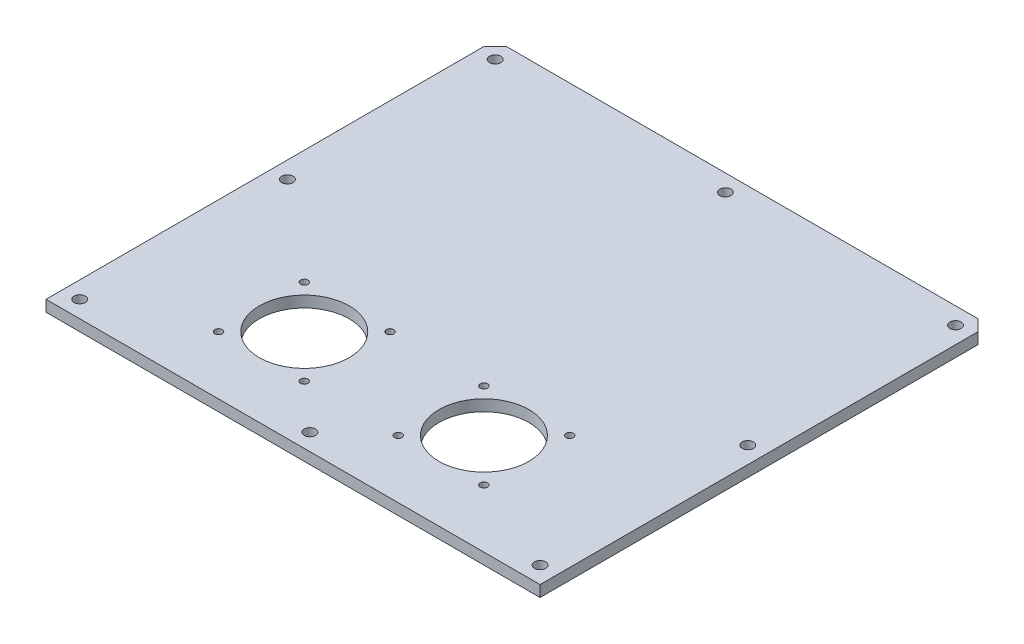
SolidWorks part; units mm, degrees
ref_plane "Спереди" through (0, 0, 0) normal (0, 0, 1) x (1, 0, 0)
ref_plane "Сверху" through (0, 0, 0) normal (0, 1, 0) x (1, 0, 0)
ref_plane "Справа" through (0, 0, 0) normal (1, 0, 0) x (0, 0, -1)
sketch "Sketch1" plane through (0, 0, 0) normal (0, 1, 0) x (1, 0, 0)
  line L0 (110, -150) -> (110, 50)
  line L1 (0, 50) -> (-110, 50)
  line L2 (-110, 50) -> (-110, -150)
  line L3 (-110, -150) -> (110, -150)
  line L4 (110, 50) -> (0, 50)
  line L5 (-110, 50) -> (-102.5, 50)
  line L6 (-102.5, 50) -> (-102.5, 42.5)
  circle A0 centre (-102.5, 42.5) radius 3
  circle A1 centre (-34.33, 42.5) radius 3
  circle A2 centre (33.84, 42.5) radius 3
  circle A3 centre (102.01, 42.5) radius 3
  circle A4 centre (-34.33, -142.5) radius 3
  circle A5 centre (33.84, -142.5) radius 3
  circle A6 centre (102.01, -142.5) radius 3
  circle A7 centre (-102.5, -142.5) radius 3
  circle A8 centre (-102.5, -19.17) radius 3
  circle A9 centre (-102.5, -80.84) radius 3
  circle A10 centre (102.5, -19.17) radius 3
  circle A11 centre (102.5, -80.84) radius 3
  circle A12 centre (102.5, 42.5) radius 3
  dimension "D1" = 4
  dimension "D2" = 2
  dimension "D3" = 3
  dimension "D4" = 2
extrude "Boss-Extrude1" add sketch "Sketch1" along normal blind 5
chamfer "Chamfer1" distance 5 angle 45 2 edges at (110, 2.5, -50) (-110, 2.5, -50)
sketch "Sketch4" plane through (0, 0, 0) normal (0, -1, 0) x (1, 0, 0)
  line L1 (0, 130) -> (-90, 130)
  line L2 (0, 135) -> (95, 135)
  line L3 (95, 135) -> (95, -35)
  line L4 (95, -35) -> (-95, -35)
  line L5 (-95, -35) -> (-95, 135)
  line L6 (-95, 135) -> (0, 135)
  line L7 (-90, 130) -> (-90, -30)
  line L8 (-90, -30) -> (90, -30)
  line L9 (90, -30) -> (90, 130)
  line L10 (90, 130) -> (0, 130)
extrude "Boss-Extrude5" add sketch "Sketch4" along normal blind 5
chamfer "Chamfer2" distance 2 angle 45 4 edges at (0, -5, -35) (95, -5, 50) (-95, -5, 50) (0, -5, 135)
sketch "Sketch9" plane through (0, 5, 0) normal (0, 1, 0) x (1, 0, 0)
  circle A0 centre (40, -105) radius 20
  circle A1 centre (-40, -105) radius 20
  circle A2 centre (59.0919, -85.9081) radius 2
  circle A3 centre (59.0919, -124.0919) radius 2
  circle A4 centre (20.9081, -124.0919) radius 2
  circle A5 centre (20.9081, -85.9081) radius 2
  circle A6 centre (-20.9081, -85.9081) radius 2
  circle A7 centre (-20.9081, -124.0919) radius 2
  circle A8 centre (-59.0919, -124.0919) radius 2
  circle A9 centre (-59.0919, -85.9081) radius 2
  point P0 (-20.9081, -85.9081)
  point P1 (59.0919, -85.9081)
  point P2 (-40, -105)
  point P16 (40, -105)
  point P29 (40, -105)
  point P37 (-40, -105)
extrude "Cut-Extrude4" cut sketch "Sketch9" against normal blind 5 contours A1 | A0
sketch "Sketch10" plane through (0, 5, 0) normal (0, 1, 0) x (1, 0, 0)
  line L0 (110, 45) -> (110, 42.5)
  line L1 (110, -150) -> (110, 45) construction
  circle A0 centre (-102.5, 42.5) radius 3
  circle A1 centre (0, 42.5) radius 3
  circle A2 centre (102.5, 42.5) radius 3
  circle A3 centre (102.5, 42.5) radius 3
  circle A4 centre (102.5, -50) radius 3
  circle A5 centre (-102.5, -50) radius 3
  circle A6 centre (-102.5, -142.5) radius 3
  circle A7 centre (0, -142.5) radius 3
  circle A8 centre (102.5, -142.5) radius 3
  dimension "D1" = 3
  dimension "D2" = 2
  dimension "D3" = 2
  dimension "D4" = 2
hole_wizard "M6 Tapped Hole1" positions "Sketch11" profile "Sketch13" tap size "M6" standard "ISO" end condition through all
sketch "Sketch11" plane through (0, 5, 0) normal (0, 1, 0) x (1, 0, 0)
  point P0 (-102.5, 42.5)
  point P3 (0, 42.5)
  point P6 (102.5, 42.5)
  point P9 (102.5, -50)
  point P12 (-102.5, -50)
  point P16 (-102.5, -142.5)
  point P19 (0, -142.5)
  point P22 (102.5, -142.5)
sketch "Sketch13" plane through (-102.5, 5, -42.5) normal (1, 0, 0) x (0, 0, 1)
  line L0 (0, 0) -> (0, 10)
  line L1 (0, 10) -> (2.5, 10)
  line L2 (2.5, 10) -> (2.5, 0)
  line L5 (2.5, 0) -> (0, 0)
  line L11 (0, -6.35) -> (0, 107.95) construction
  dimension "Thru Tap Drill Dia." = 5
  dimension "Thru Tap Drill Depth" = 10
cosmetic thread "Hole Thread1" parameters "D2"=6
cosmetic thread "Hole Thread2" parameters "D2"=6
cosmetic thread "Hole Thread3" parameters "D2"=6
cosmetic thread "Hole Thread4" parameters "D2"=6
cosmetic thread "Hole Thread5" parameters "D2"=6
cosmetic thread "Hole Thread14" parameters "D2"=6
cosmetic thread "Hole Thread15" parameters "D2"=6
cosmetic thread "Hole Thread16" parameters "D2"=6
sketch "Sketch15" plane through (0, 5, 0) normal (0, 1, 0) x (1, 0, 0)
  circle A1 centre (-59.0919, -85.9081) radius 2
  circle A2 centre (-20.9081, -85.9081) radius 2
  circle A3 centre (-20.9081, -124.0919) radius 2
  circle A4 centre (-59.0919, -124.0919) radius 2
  circle A5 centre (20.9081, -124.0919) radius 2
  circle A6 centre (20.9081, -85.9081) radius 2
  circle A7 centre (59.0919, -124.0919) radius 2
  circle A8 centre (59.0919, -85.9081) radius 2
  dimension "D1" = 4
hole_wizard "M4 Tapped Hole1" positions "Sketch18" profile "Sketch19" tap size "M4" standard "ISO"
sketch "Sketch18" plane through (0, 5, 0) normal (0, 1, 0) x (1, 0, 0)
  point P0 (-59.0919, -85.9081)
  point P3 (-20.9081, -85.9081)
  point P6 (-20.9081, -124.0919)
  point P9 (-59.0919, -124.0919)
  point P12 (20.9081, -85.9081)
  point P15 (59.0919, -85.9081)
  point P18 (59.0919, -124.0919)
  point P21 (20.9081, -124.0919)
sketch "Sketch19" plane through (-59.0919, 5, 85.9081) normal (1, 0, 0) x (0, 0, 1)
  line L0 (0, 0) -> (0, 5.9914)
  line L1 (0, 5.9914) -> (1.65, 5)
  line L2 (1.65, 5) -> (1.65, 0)
  line L5 (1.65, 0) -> (0, 0)
  line L10 (0, 5.9914) -> (-1.65, 5) construction
  line L11 (0, -6.35) -> (0, 107.95) construction
  dimension "Tap Drill Dia." = 3.3
  dimension "Tap Drill Depth" = 5
  dimension "Drill Angle" = 118
cosmetic thread "Hole Thread6" parameters "D1"=5, "D2"=4
cosmetic thread "Hole Thread7" parameters "D1"=5, "D2"=4
cosmetic thread "Hole Thread8" parameters "D1"=5, "D2"=4
cosmetic thread "Hole Thread9" parameters "D1"=5, "D2"=4
cosmetic thread "Hole Thread10" parameters "D1"=5, "D2"=4
cosmetic thread "Hole Thread11" parameters "D1"=5, "D2"=4
cosmetic thread "Hole Thread12" parameters "D1"=5, "D2"=4
cosmetic thread "Hole Thread13" parameters "D1"=5, "D2"=4
